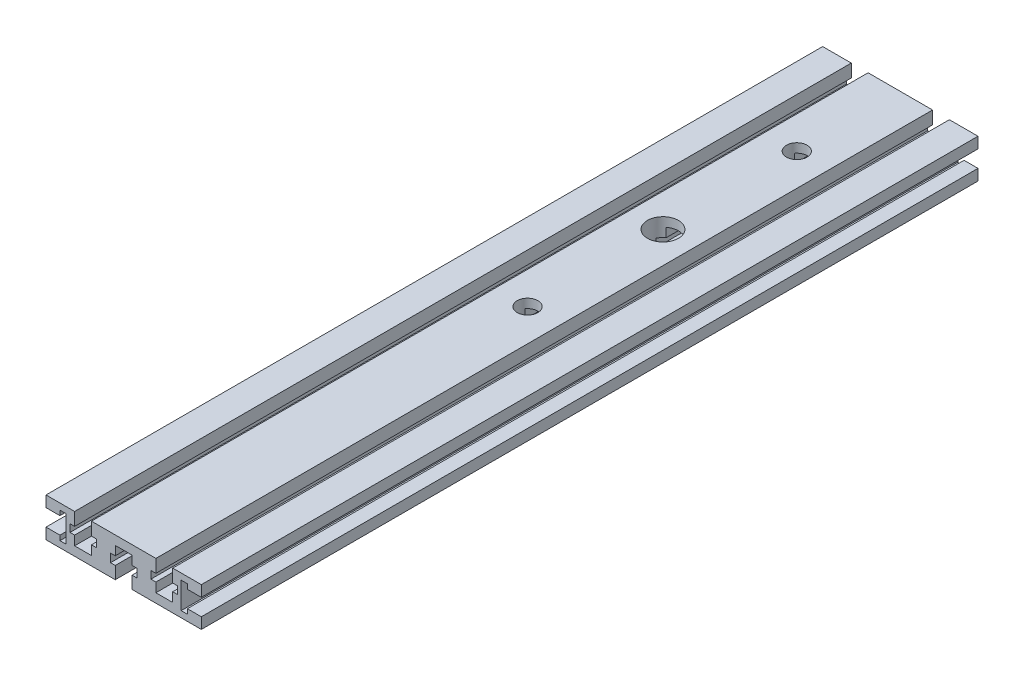
SolidWorks part; units mm, degrees
ref_plane "前视" through (0, 0, 0) normal (0, 0, 1) x (1, 0, 0)
ref_plane "上视" through (0, 0, 0) normal (0, 1, 0) x (1, 0, 0)
ref_plane "右视" through (0, 0, 0) normal (1, 0, 0) x (0, 0, -1)
sketch "草图1" plane through (0, 0, 0) normal (0, 0, 1) x (1, 0, 0)
  line L0 (0, 0) -> (26.75, 0)
  line L1 (0, 0) -> (0, 4.25)
  line L2 (0, 4.25) -> (5.3867, 4.25)
  line L3 (5.3867, 4.25) -> (5.3867, 2.4)
  line L4 (5.3867, 2.4) -> (7.8, 2.4)
  line L5 (7.8, 2.4) -> (7.8, 12.6)
  line L6 (7.8, 12.6) -> (5.3867, 12.6)
  line L7 (5.3867, 12.6) -> (5.3867, 10.75)
  line L8 (5.3867, 10.75) -> (0, 10.75)
  line L9 (0, 10.75) -> (0, 15)
  line L10 (0, 15) -> (11.0524, 15)
  line L11 (11.0524, 15) -> (11.0524, 10.0038)
  line L12 (11.0524, 10.0038) -> (9.2662, 10.0038)
  line L13 (9.2662, 10.0038) -> (9.2662, 7.0947)
  line L14 (9.2662, 7.0947) -> (11.0524, 7.0947)
  line L15 (11.0524, 7.0947) -> (11.0524, 3.5)
  line L16 (11.0524, 3.5) -> (17.5524, 3.5)
  line L17 (17.5524, 3.5) -> (17.5524, 7.0947)
  line L18 (17.5524, 7.0947) -> (19.4662, 7.0947)
  line L19 (19.4662, 7.0947) -> (19.4662, 10.0038)
  line L20 (19.4662, 10.0038) -> (17.5524, 10.0038)
  line L21 (17.5524, 10.0038) -> (17.5524, 15)
  line L22 (17.5524, 15) -> (30, 15)
  line L23 (26.75, 0) -> (26.75, 4.7964)
  line L24 (26.75, 4.7964) -> (24.9265, 4.7964)
  line L25 (24.9265, 4.7964) -> (24.9265, 8.0234)
  line L26 (24.9265, 8.0234) -> (26.75, 8.0234)
  line L27 (26.75, 8.0234) -> (26.75, 11.5)
  line L28 (26.75, 11.5) -> (30, 11.5)
  line L29 (30, 15) -> (42.4476, 15)
  line L30 (30, 11.5) -> (33.25, 11.5)
  line L32 (33.25, 8.0234) -> (33.25, 11.5)
  line L33 (35.0735, 8.0234) -> (33.25, 8.0234)
  line L34 (35.0735, 4.7964) -> (35.0735, 8.0234)
  line L35 (33.25, 4.7964) -> (35.0735, 4.7964)
  line L36 (33.25, 0) -> (33.25, 4.7964)
  line L37 (42.4476, 10.0038) -> (42.4476, 15)
  line L38 (40.5338, 10.0038) -> (42.4476, 10.0038)
  line L39 (40.5338, 7.0947) -> (40.5338, 10.0038)
  line L40 (42.4476, 7.0947) -> (40.5338, 7.0947)
  line L41 (42.4476, 3.5) -> (42.4476, 7.0947)
  line L42 (48.9476, 3.5) -> (42.4476, 3.5)
  line L43 (48.9476, 7.0947) -> (48.9476, 3.5)
  line L44 (50.7338, 7.0947) -> (48.9476, 7.0947)
  line L45 (50.7338, 10.0038) -> (50.7338, 7.0947)
  line L46 (48.9476, 10.0038) -> (50.7338, 10.0038)
  line L47 (48.9476, 15) -> (48.9476, 10.0038)
  line L48 (60, 15) -> (48.9476, 15)
  line L49 (60, 10.75) -> (60, 15)
  line L50 (54.6133, 10.75) -> (60, 10.75)
  line L51 (54.6133, 12.6) -> (54.6133, 10.75)
  line L52 (52.2, 12.6) -> (54.6133, 12.6)
  line L53 (52.2, 2.4) -> (52.2, 12.6)
  line L54 (54.6133, 2.4) -> (52.2, 2.4)
  line L55 (54.6133, 4.25) -> (54.6133, 2.4)
  line L56 (60, 4.25) -> (54.6133, 4.25)
  line L57 (60, 0) -> (60, 4.25)
  line L58 (60, 0) -> (33.25, 0)
  dimension "D1" = 6.5
  dimension "D2" = 7.8
  dimension "D3" = 15
  dimension "D4" = 6.5
  dimension "D5" = 11.5
  dimension "D6" = 2.4
  dimension "D7" = 10.2
  dimension "D8" = 15
  dimension "D9" = 2.4
  dimension "D10" = 4.25
  dimension "D11" = 11.5
  dimension "D12" = 60
  dimension "D13" = 3.25
extrude "凸台-拉伸1" add sketch "草图1" along normal blind 300
hole_wizard "Ø12.0 (12) 直径孔1" positions "草图3" profile "草图2" hole size "Ø12.0" standard "Gb" end condition through all
sketch "草图3" plane through (0, 15, 0) normal (0, 1, 0) x (1, 0, 0)
  line L0 (42.4476, -300) -> (17.5524, -300) construction
  point P0 (30.3155, -92)
  dimension "D1" = 208
sketch "草图2" plane through (30.3155, 15, 92) normal (1, 0, 0) x (0, 0, 1)
  line L0 (0, 0) -> (0, 15)
  line L1 (0, 15) -> (6, 15)
  line L2 (6, 15) -> (6, 0)
  line L5 (6, 0) -> (0, 0)
  line L11 (0, -6.35) -> (0, 107.95) construction
  dimension "通孔孔直径" = 12
  dimension "通孔孔深度" = 15
hole_wizard "Ø8.0 (8) 直径孔1" positions "草图5" profile "草图4" hole size "Ø8.0" standard "Gb" end condition through all
sketch "草图5" plane through (0, 15, 0) normal (0, 1, 0) x (1, 0, 0)
  line L0 (0, -300) -> (0, 0) construction
  line L7 (42.4476, -300) -> (17.5524, -300) construction
  point P0 (30, -40)
  point P2 (30, -144)
  point P30 (30, -300)
  dimension "D1" = 30
  dimension "D2" = 260
  dimension "D3" = 156
sketch "草图4" plane through (30, 15, 40) normal (1, 0, 0) x (0, 0, 1)
  line L0 (0, 0) -> (0, 15)
  line L1 (0, 15) -> (4, 15)
  line L2 (4, 15) -> (4, 0)
  line L5 (4, 0) -> (0, 0)
  line L11 (0, -6.35) -> (0, 107.95) construction
  dimension "通孔孔直径" = 8
  dimension "通孔孔深度" = 15
hole_wizard "Ø6.0 (6) 直径孔1" positions "草图7" profile "草图6" hole size "Ø6.0" standard "Gb" end condition through all
sketch "草图7" plane through (0, 3.5, 0) normal (0, 1, 0) x (1, 0, 0)
  line L0 (48.9476, 0) -> (42.4476, 0) construction
  line L1 (42.4476, -300) -> (42.4476, 0) construction
  point P0 (45.6976, -7.5)
  dimension "D1" = 7.5
  dimension "D2" = 3.25
sketch "草图6" plane through (45.6976, 3.5, 7.5) normal (1, 0, 0) x (0, 0, 1)
  line L0 (0, 0) -> (0, 3.5)
  line L1 (0, 3.5) -> (3, 3.5)
  line L2 (3, 3.5) -> (3, 0)
  line L5 (3, 0) -> (0, 0)
  line L11 (0, -6.35) -> (0, 107.95) construction
  dimension "通孔孔直径" = 6
  dimension "通孔孔深度" = 3.5
